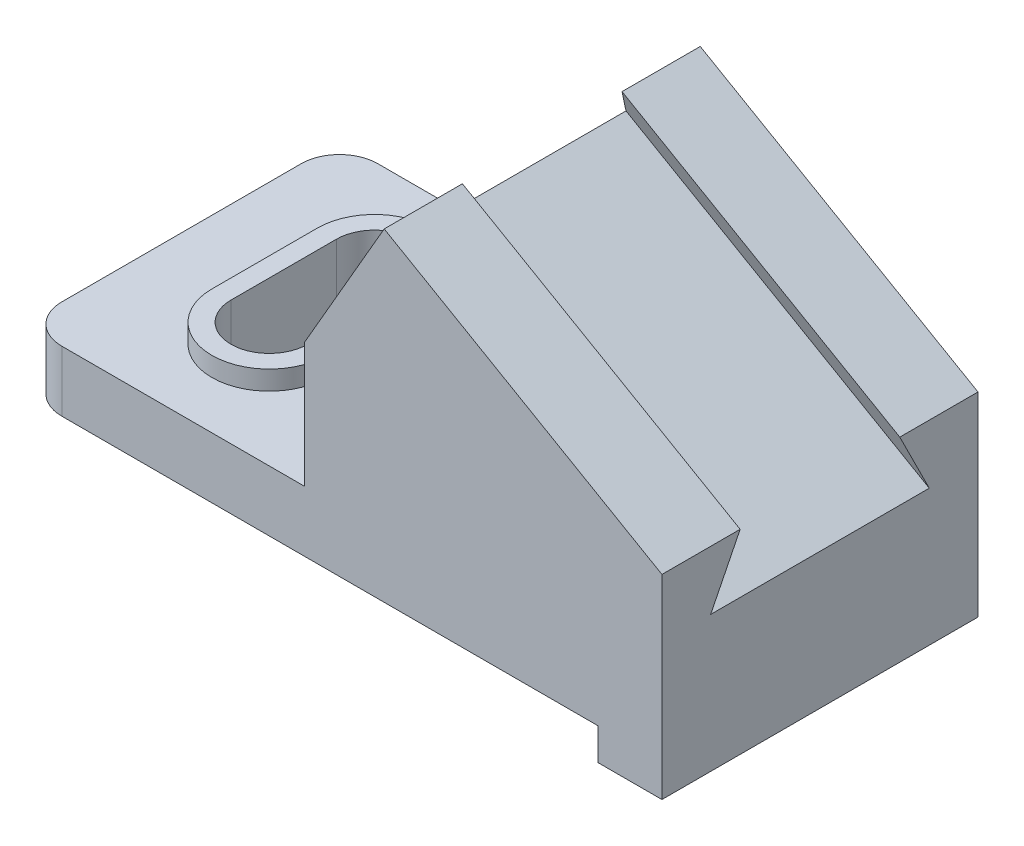
SolidWorks part; units mm, degrees
ref_plane "Front Plane" through (0, 0, 0) normal (0, 0, 1) x (1, 0, 0)
ref_plane "Top Plane" through (0, 0, 0) normal (0, 1, 0) x (1, 0, 0)
ref_plane "Right Plane" through (0, 0, 0) normal (1, 0, 0) x (0, 0, -1)
sketch "Sketch1" plane through (0, 0, 0) normal (0, 0, 1) x (1, 0, 0)
  line L0 (44, 34) -> (56.5, 55.6506)
  line L1 (90, 0) -> (100, 0)
  line L2 (90, 0) -> (90, 5)
  line L3 (90, 5) -> (44, 5)
  line L4 (6, 14.5) -> (44, 14.5)
  line L5 (44, 14.5) -> (44, 34)
  line L6 (56.5, 55.6506) -> (100, 30.5359)
  line L7 (100, 0) -> (100, 21.0359)
  line L8 (44, 5) -> (6, 5)
  line L9 (6, 5) -> (0, 5)
  line L10 (100, 30.5359) -> (100, 21.0359)
  line L11 (0, 5) -> (0, 14.5)
  line L12 (0, 14.5) -> (6, 14.5)
  point P14 (0, 0)
  point P15 (0, 0)
  dimension "D1" = 94
  dimension "D2" = 10
  dimension "D3" = 5
  dimension "D4" = 56
  dimension "D5" = 44
  dimension "D6" = 25
  dimension "D7" = 60
  dimension "D8" = 9.5
  dimension "D9" = 19.5
extrude "Boss-Extrude1" add sketch "Sketch1" along normal mid plane 49.5
sketch "Sketch2" plane through (0, 14.5, 0) normal (0, 1, 0) x (1, 0, 0)
  line L0 (44, 24.75) -> (0, 24.75) construction
  line L3 (44, -24.75) -> (0, -24.75) construction
  line L5 (22, 8.25) -> (22, -8.25) construction
  line L6 (28, 8.25) -> (28, -8.25)
  line L7 (16, 8.25) -> (16, -8.25)
  line L8 (22, 8.25) -> (22, -8.25) construction
  line L9 (31, 8.25) -> (31, -8.25)
  line L10 (13, 8.25) -> (13, -8.25)
  line L11 (0, -24.75) -> (0, 24.75) construction
  arc A0 (28, 8.25) -> (16, 8.25) centre (22, 8.25) ccw
  arc A1 (16, -8.25) -> (28, -8.25) centre (22, -8.25) ccw
  arc A2 (31, 8.25) -> (13, 8.25) centre (22, 8.25) ccw
  arc A3 (13, -8.25) -> (31, -8.25) centre (22, -8.25) ccw
  point P7 (22, -24.75)
  point P9 (22, 0)
  point P16 (22, 0)
  dimension "D1" = 16.5
  dimension "D2" = 18
  dimension "D3" = 16.5
  dimension "D4" = 3
  dimension "D5" = 22
extrude "Boss-Extrude2" add sketch "Sketch2" along normal blind 3
sketch "Sketch3" plane through (0, 14.5, 0) normal (0, 1, 0) x (1, 0, 0)
  line L2 (28, -8.25) -> (28, 8.25)
  line L3 (16, 8.25) -> (16, -8.25)
  line L4 (28, -8.25) -> (28, 8.25)
  line L5 (16, 8.25) -> (16, -8.25)
  arc A2 (28, 8.25) -> (16, 8.25) centre (22, 8.25) ccw
  arc A3 (16, -8.25) -> (28, -8.25) centre (22, -8.25) ccw
  arc A4 (28, 8.25) -> (16, 8.25) centre (22, 8.25) ccw
  arc A5 (16, -8.25) -> (28, -8.25) centre (22, -8.25) ccw
  dimension "D1" = 0
extrude "Cut-Extrude1" cut sketch "Sketch3" against normal through all
sketch "Sketch4" plane through (18.2776, -10.5526, 0) normal (-0.866, 0.5, 0) x (0, 0, 1)
  line L1 (24.75, 76.4449) -> (-24.75, 76.4449) construction
  line L2 (-12.5, 76.4449) -> (12.5, 76.4449)
  line L4 (-17.1188, 68.4449) -> (17.1188, 68.4449)
  line L5 (-12.5, 76.4449) -> (-17.1188, 68.4449)
  line L6 (0, 76.4449) -> (0, 42.5168) construction
  line L7 (12.5, 76.4449) -> (17.1188, 68.4449)
  dimension "D1" = 60
  dimension "D2" = 25
  dimension "D3" = 8
extrude "Cut-Extrude2" cut sketch "Sketch4" against normal through all
fillet "Fillet1" radius 6 2 edges at (0, 9.75, -24.75) (0, 9.75, 24.75)
